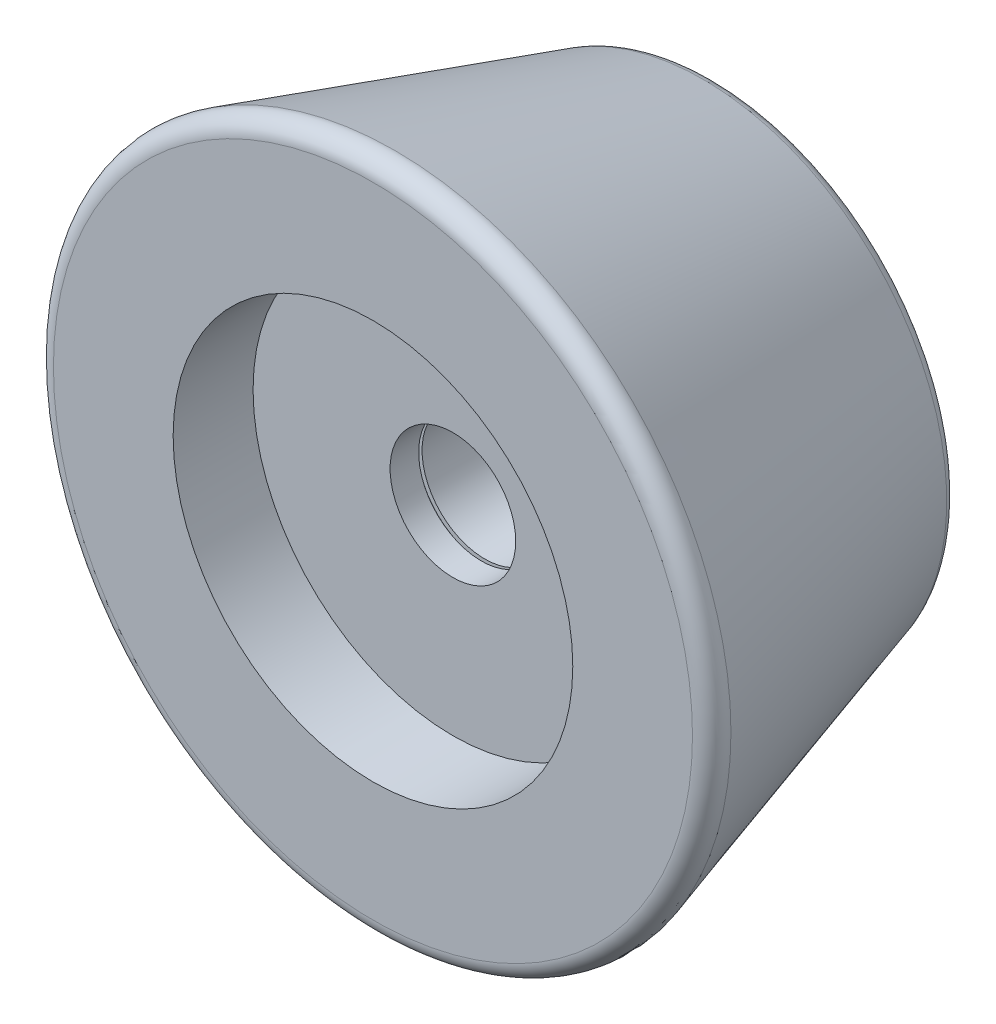
SolidWorks part; units mm, degrees
ref_plane "Front Plane" through (0, 0, 0) normal (0, 0, 1) x (1, 0, 0)
ref_plane "Top Plane" through (0, 0, 0) normal (0, 1, 0) x (1, 0, 0)
ref_plane "Right Plane" through (0, 0, 0) normal (1, 0, 0) x (0, 0, -1)
sketch "Sketch2" plane through (0, 0, 0) normal (0, 1, 0) x (1, 0, 0)
  line L0 (0, 0) -> (0, 27.8285) construction
  line L1 (5.125, 0) -> (10.5, 0)
  line L2 (10.5, 0) -> (15, -15)
  line L3 (15, -15) -> (8.75, -15)
  line L6 (2.75, -11.5) -> (2.75, -10.25)
  line L7 (2.75, -3.25) -> (5.125, -3.25)
  line L8 (5.125, -3.25) -> (5.125, 0)
  line L9 (2.75, -11.5) -> (8.75, -11.5)
  line L10 (8.75, -11.5) -> (8.75, -15)
  line L11 (2.75, -10.1) -> (2.75, -3.25)
  line L12 (2.75, -10.25) -> (2.95, -10.25)
  line L14 (2.75, -10.1) -> (2.95, -10.1)
  line L15 (2.95, -10.25) -> (2.95, -10.1)
  dimension "D1" = 30
  dimension "D2" = 21
  dimension "D3" = 6
  dimension "D4" = 5.5
  dimension "D5" = 15
  dimension "D6" = 3.5
  dimension "D7" = 3.25
  dimension "D8" = 10.25
  dimension "D9" = 0.15
  dimension "D10" = 1.25
  dimension "D11" = 0.2
revolve "Revolve1" add sketch "Sketch2" angle 360 about L0
fillet "Fillet1" radius 0.75 2 edges at (15, 0, 15) (10.5, 0, 0)
